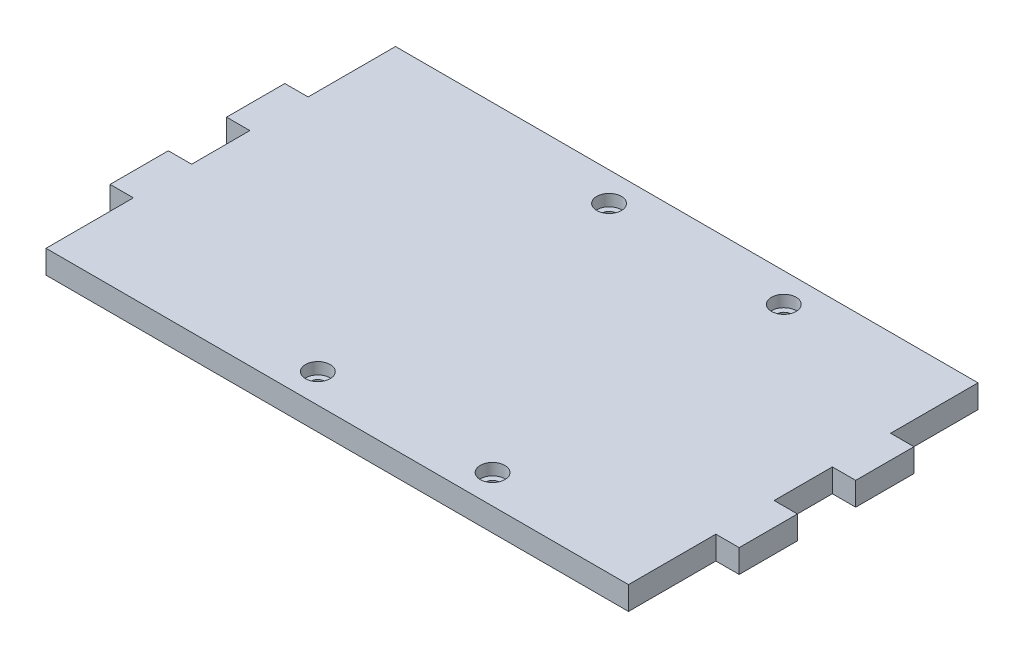
SolidWorks part; units mm, degrees
ref_plane "Front Plane" through (0, 0, 0) normal (0, 0, 1) x (1, 0, 0)
ref_plane "Top Plane" through (0, 0, 0) normal (0, 1, 0) x (1, 0, 0)
ref_plane "Right Plane" through (0, 0, 0) normal (1, 0, 0) x (0, 0, -1)
sketch "Sketch1" plane through (0, 0, 0) normal (0, 1, 0) x (1, 0, 0)
  line L0 (0, 45) -> (0, -45) construction
  line L1 (-75, -45) -> (75, -45)
  line L2 (-75, -45) -> (-75, -22.5)
  line L3 (-75, 45) -> (75, 45)
  line L4 (75, -45) -> (75, -22.5)
  line L5 (-75, -45) -> (75, 45) construction
  line L6 (-75, 45) -> (75, -45) construction
  line L7 (75, 22.5) -> (81, 22.5)
  line L9 (75, 7.5) -> (81, 7.5)
  line L10 (81, 22.5) -> (81, 7.5)
  line L11 (75, -7.5) -> (81, -7.5)
  line L13 (75, -22.5) -> (81, -22.5)
  line L14 (81, -7.5) -> (81, -22.5)
  line L15 (-75, -22.5) -> (-81, -22.5)
  line L16 (-81, -7.5) -> (-81, -22.5)
  line L17 (-75, -7.5) -> (-81, -7.5)
  line L19 (-75, 7.5) -> (-81, 7.5)
  line L20 (-81, 22.5) -> (-81, 7.5)
  line L21 (-75, 22.5) -> (-81, 22.5)
  line L23 (-75, 22.5) -> (-75, 45)
  line L24 (-75, -7.5) -> (-75, 7.5)
  line L25 (75, 22.5) -> (75, 45)
  line L26 (75, -7.5) -> (75, 7.5)
  point P0 (0, 0)
  dimension "D1" = 150
  dimension "D2" = 90
  dimension "D3" = 6
  dimension "D4" = 6
  dimension "D5" = 15
  dimension "D6" = 15
  dimension "D7" = 7.5
  dimension "D8" = 7.5
extrude "Boss-Extrude1" add sketch "Sketch1" along normal blind 6
sketch "Sketch2" plane through (0, 6, 0) normal (0, 1, 0) x (1, 0, 0)
  line L0 (-75, -45) -> (75, -45) construction
  line L4 (37.5, 45) -> (37.5, -45) construction
  line L5 (75, 45) -> (-75, 45) construction
  line L6 (75, 22.5) -> (75, 45) construction
  circle A0 centre (32.5, 37.5) radius 1.75
  circle A1 centre (32.5, -37.5) radius 1.75
  circle A2 centre (-12.5, 37.5) radius 1.75
  circle A3 centre (-12.5, -37.5) radius 1.75
  dimension "D2" = 5
  dimension "D4" = 75
  dimension "D5" = 45
  dimension "D6" = 45
  dimension "D1" = 37.5
  dimension "D3" = 7.5
extrude "Cut-Extrude1" cut sketch "Sketch2" against normal up to surface (6 mm away) contours A0 | A2 | A1 | A3 up to face at (0, 0, 0)
sketch "Sketch3" plane through (0, 6, 0) normal (0, 1, 0) x (1, 0, 0)
  circle A0 centre (-12.5, 37.5) radius 3.175
  circle A1 centre (32.5, 37.5) radius 3.175
  circle A2 centre (32.5, -37.5) radius 3.175
  circle A3 centre (-12.5, -37.5) radius 3.175
extrude "Cut-Extrude2" cut sketch "Sketch3" against normal blind 3
